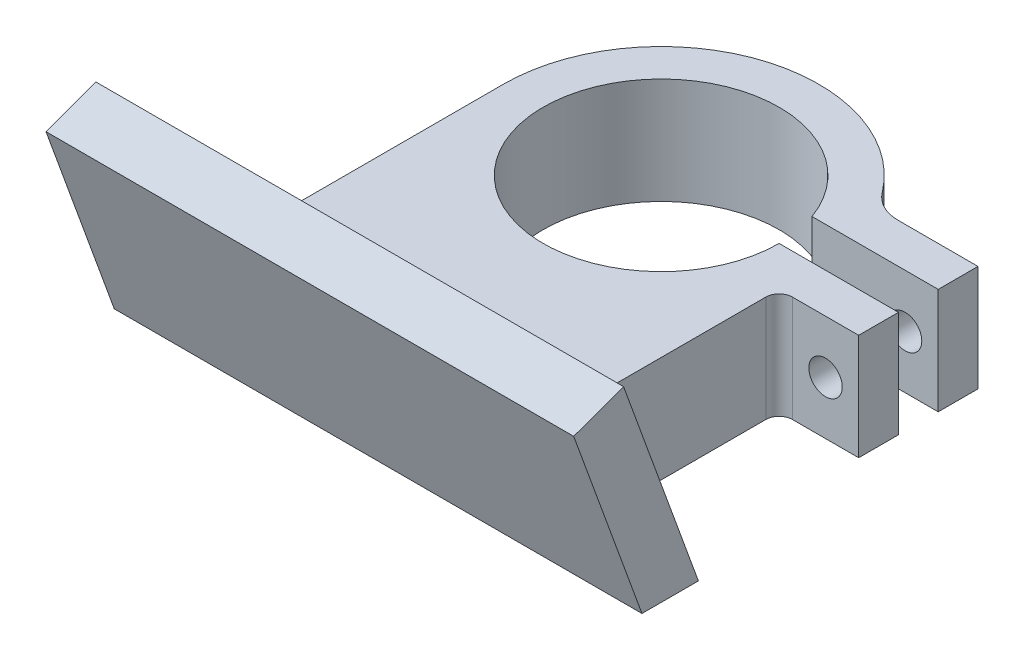
SolidWorks part; units mm, degrees
ref_plane "Front Plane" through (0, 0, 0) normal (0, 0, 1) x (1, 0, 0)
ref_plane "Top Plane" through (0, 0, 0) normal (0, 1, 0) x (1, 0, 0)
ref_plane "Right Plane" through (0, 0, 0) normal (1, 0, 0) x (0, 0, -1)
sketch "Sketch1" plane through (0, 0, 0) normal (0, 1, 0) x (1, 0, 0)
  line L0 (0, -55) -> (0, 55) construction
  line L1 (-55, 0) -> (55, 0) construction
  line L2 (-15.113, 0) -> (-15.113, -25.4)
  line L3 (-15.113, -25.4) -> (15.113, -25.4)
  line L4 (15.113, -25.4) -> (15.113, -3.81)
  line L5 (15.113, 0) -> (22.733, 0)
  line L6 (22.733, 0) -> (22.733, -3.81)
  line L7 (22.733, -3.81) -> (15.113, -3.81)
  line L8 (10.6415, 3.81) -> (22.733, 3.81)
  line L9 (22.733, 3.81) -> (22.733, 7.62)
  line L10 (22.733, 7.62) -> (13.0514, 7.62)
  line L11 (15.113, 0) -> (11.303, 0)
  arc A0 (10.6415, 3.81) -> (11.303, 0) centre (0, 0) ccw
  arc A1 (13.0514, 7.62) -> (-15.113, 0) centre (0, 0) ccw
  dimension "D1" = 22.606
  dimension "D2" = 3.81
  dimension "D3" = 25.4
  dimension "D7" = 3.81
  dimension "D4" = 3.81
  dimension "D5" = 7.62
  dimension "D6" = 3.81
  dimension "D8" = 3.81
extrude "Boss-Extrude1" add sketch "Sketch1" along normal blind 10.16
sketch "Sketch2" plane through (-15.113, 0, 0) normal (-1, 0, 0) x (0, 0, 1)
  line L0 (25.4, 10.16) -> (21.7021, 0)
  line L1 (0, 0) -> (25.4, 0) construction
  line L2 (25.4, 10.16) -> (25.4, 0)
  line L3 (25.4, 0) -> (21.7021, 0)
  dimension "D1" = 20
extrude "Cut-Extrude1" cut sketch "Sketch2" against normal up to next
sketch "Sketch3" plane through (0, -6.9749, 19.1634) normal (0, -0.342, 0.9397) x (1, 0, 0)
  line L12 (-25.273, 7.4225) -> (25.273, 7.4225)
  line L13 (15.113, 7.4225) -> (-15.113, 7.4225) construction
  line L16 (25.273, -2.7375) -> (25.273, 28.3946)
  line L17 (25.273, 28.3946) -> (-25.273, 28.3946)
  line L18 (-25.273, 28.3946) -> (-25.273, -2.7375)
  line L19 (-25.273, -2.7375) -> (25.273, -2.7375)
  line L20 (25.273, 7.4225) -> (25.273, 28.3946)
  line L21 (25.273, 28.3946) -> (-25.273, 28.3946)
  line L22 (-25.273, 28.3946) -> (-25.273, 7.4225)
  dimension "D1" = 10.16
extrude "Boss-Extrude2" add sketch "Sketch3" along normal blind 5.08
sketch "Sketch4" plane through (-25.273, 0, 0) normal (-1, 0, 0) x (0, 0, 1)
  line L0 (27.1081, 0) -> (26.4757, -1.7375)
  line L1 (55, 0) -> (-55, 0) construction
  line L2 (33.6486, 17.9698) -> (26.4757, -1.7375) construction
  line L3 (26.4757, -1.7375) -> (21.7021, 0)
  line L4 (26.4757, -1.7375) -> (21.7021, 0) construction
  line L5 (21.7021, 0) -> (27.1081, 0)
extrude "Cut-Extrude2" cut sketch "Sketch4" against normal up to next
fillet "Fillet1" radius 5.08 3 edges at (15.113, 5.08, 23.551) (-15.113, 5.08, 23.551) (0, 10.16, 25.4)
fillet "Fillet2" radius 3.81 1 edges at (13.0514, 5.08, -7.62)
fillet "Fillet3" radius 1.27 1 edges at (15.113, 5.08, 3.81)
sketch "Sketch5" plane through (0, 0, 3.81) normal (0, 0, 1) x (1, 0, 0)
  line L0 (16.383, 10.16) -> (22.733, 10.16) construction
  line L1 (22.733, 10.16) -> (22.733, 0) construction
  circle A0 centre (19.558, 5.08) radius 1.6
  point P5 (19.558, 10.16)
  point P8 (22.733, 5.08)
  dimension "D1" = 3.2
extrude "Cut-Extrude3" cut sketch "Sketch5" against normal through all
